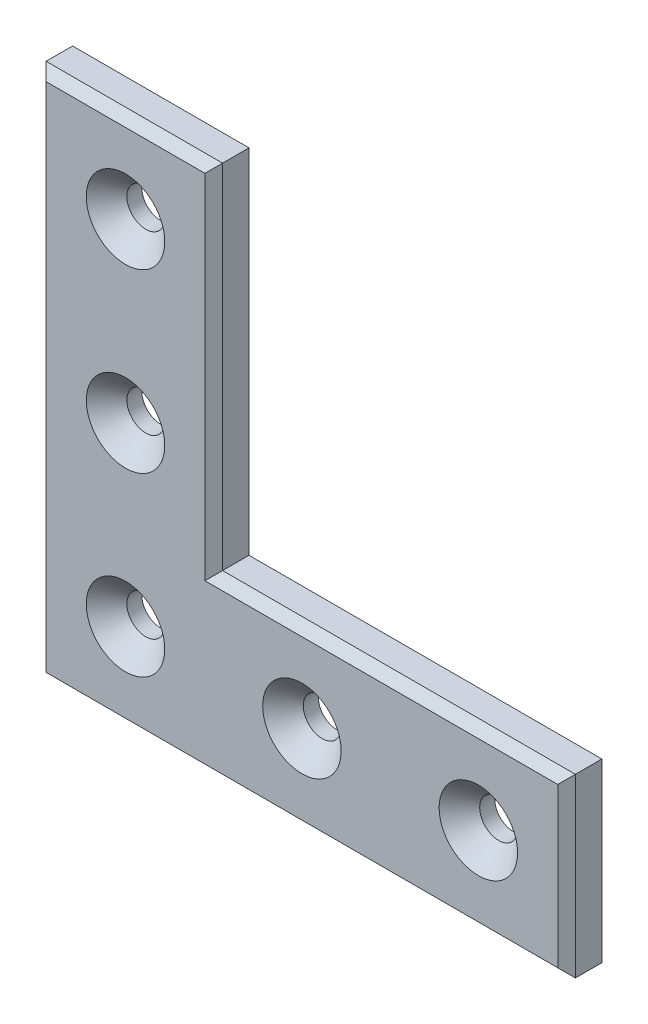
SolidWorks part; units mm, degrees
ref_plane "Front Plane" through (0, 0, 0) normal (0, 0, 1) x (1, 0, 0)
ref_plane "Top Plane" through (0, 0, 0) normal (0, 1, 0) x (1, 0, 0)
ref_plane "Right Plane" through (0, 0, 0) normal (1, 0, 0) x (0, 0, -1)
sketch "Sketch1" plane through (0, 0, 0) normal (0, 0, 1) x (1, 0, 0)
  line L4 (50, -10) -> (50, 10)
  line L5 (50, 10) -> (10, 10)
  line L6 (-10, 0) -> (50, 0) construction
  line L8 (-10, 10) -> (-10, 50)
  line L9 (-10, 50) -> (10, 50)
  line L10 (10, 10) -> (10, 50)
  line L11 (10, 10) -> (-10, 10) construction
  line L12 (-10, 10) -> (-10, -10)
  line L13 (0, 50) -> (0, 0) construction
  line L14 (-10, -10) -> (50, -10)
  circle A0 centre (0, 20) radius 2.15
  circle A1 centre (20, 0) radius 2.15
  circle A3 centre (0, 40) radius 2.15
  circle A4 centre (0, 0) radius 2.15
  circle A5 centre (40, 0) radius 2.15
  point P0 (0, 0)
  point P10 (0, 50)
  dimension "D3" = 4.3
  dimension "D8" = 20
  dimension "D9" = 10
  dimension "D1" = 20
  dimension "D2" = 20
  dimension "D4" = 20
  dimension "D5" = 20
  dimension "D6" = 20
  dimension "D7" = 10
extrude "Boss-Extrude1" add sketch "Sketch1" along normal blind 4
sketch "Sketch2" plane through (0, 0, 0) normal (0, 0, -1) x (-1, 0, 0)
  line L0 (0, 40) -> (0, 20) construction
  line L1 (-40, 0) -> (-20, 0) construction
  line L3 (-2.9, 14) -> (2.9, 14)
  line L4 (-2.9, 14) -> (-2.9, 46)
  line L5 (-2.9, 46) -> (2.9, 46)
  line L6 (2.9, 14) -> (2.9, 46)
  line L7 (-2.9, 14) -> (2.9, 46) construction
  line L8 (-2.9, 46) -> (2.9, 14) construction
  line L9 (-46, -2.9) -> (-14, -2.9)
  line L10 (-46, -2.9) -> (-46, 2.9)
  line L11 (-46, 2.9) -> (-14, 2.9)
  line L12 (-14, -2.9) -> (-14, 2.9)
  line L13 (-46, -2.9) -> (-14, 2.9) construction
  line L14 (-46, 2.9) -> (-14, -2.9) construction
  circle A0 centre (0, 40) radius 2.15 construction
  circle A1 centre (0, 20) radius 2.15 construction
  circle A2 centre (-20, 0) radius 2.15 construction
  circle A3 centre (-40, 0) radius 2.15 construction
  circle A4 centre (0, 40) radius 2.15
  circle A5 centre (0, 20) radius 2.15
  circle A6 centre (-20, 0) radius 2.15
  circle A7 centre (-40, 0) radius 2.15
  point P8 (0, 30)
  point P13 (-30, 0)
  dimension "D1" = 5.8
  dimension "D2" = 6
  dimension "D3" = 6
chamfer "Chamfer1" distance 1 angle 45 6 edges at (50, 0, 4) (20, -10, 4) (-10, 20, 4) (0, 50, 4) (10, 30, 4) (30, 10, 4)
chamfer "Chamfer2" distance 2.3 angle 45 5 edges at (22.15, 0, 4) (42.15, 0, 4) (2.15, 0, 4) (2.15, 20, 4) (2.15, 40, 4)
